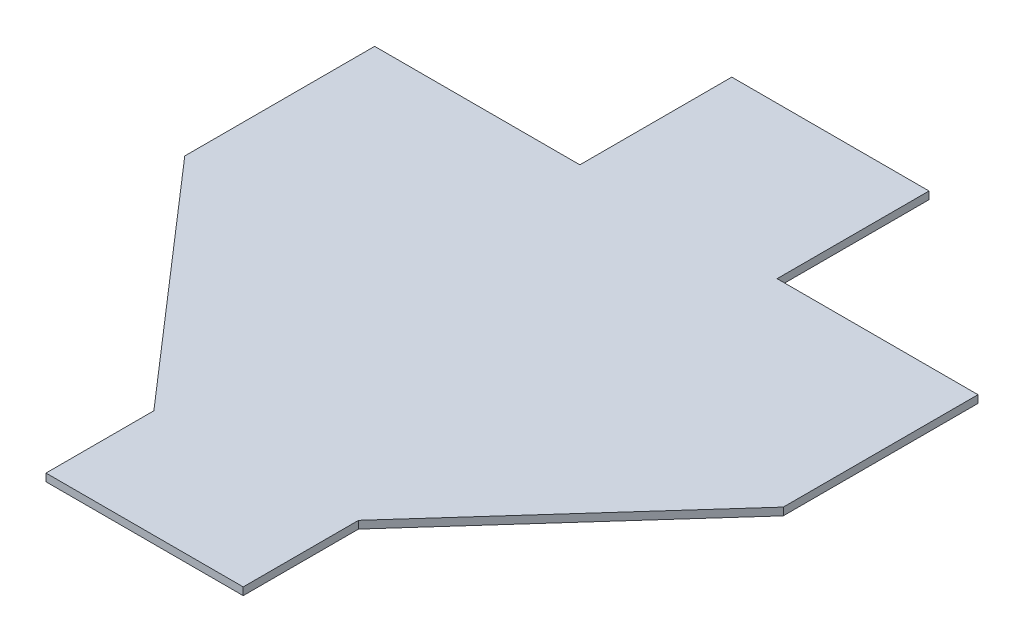
SolidWorks part; units mm, degrees
ref_plane "Front Plane" through (0, 0, 0) normal (0, 0, 1) x (1, 0, 0)
ref_plane "Top Plane" through (0, 0, 0) normal (0, 1, 0) x (1, 0, 0)
ref_plane "Right Plane" through (0, 0, 0) normal (1, 0, 0) x (0, 0, -1)
sketch "Sketch1" plane through (0, 0, 0) normal (0, 1, 0) x (1, 0, 0)
  line L5 (-17.1012, 62.0267) -> (-17.1012, 42.0267)
  line L6 (-44.1194, 42.0267) -> (-44.1194, 17.0267)
  line L7 (35.3139, 42.0267) -> (35.3139, 16.3953)
  line L8 (-44.1194, 42.0267) -> (-17.1012, 42.0267)
  line L9 (-44.1194, 17.0267) -> (-4.7603, -28.2597)
  line L10 (8.8624, 62.0267) -> (8.8624, 42.0267)
  line L11 (8.8624, 42.0267) -> (35.3139, 42.0267)
  line L12 (8.8624, 62.0267) -> (-17.1012, 62.0267)
  line L13 (35.3139, 16.3953) -> (-4.7603, -28.2597)
extrude "Boss-Extrude1" add sketch "Sketch1" along normal blind 1
sketch "Sketch2" plane through (0, 1, 0) normal (0, 1, 0) x (1, 0, 0)
  line L0 (8.8624, -28.2597) -> (-17.1012, -28.2597)
  line L2 (8.8624, 62.0267) -> (8.8624, -28.2597)
  line L3 (-17.1012, 42.0267) -> (-17.1012, -28.2597)
  line L4 (-17.1012, 42.0267) -> (8.8624, 62.0267)
extrude "Boss-Extrude2" add sketch "Sketch2" against normal blind 1
